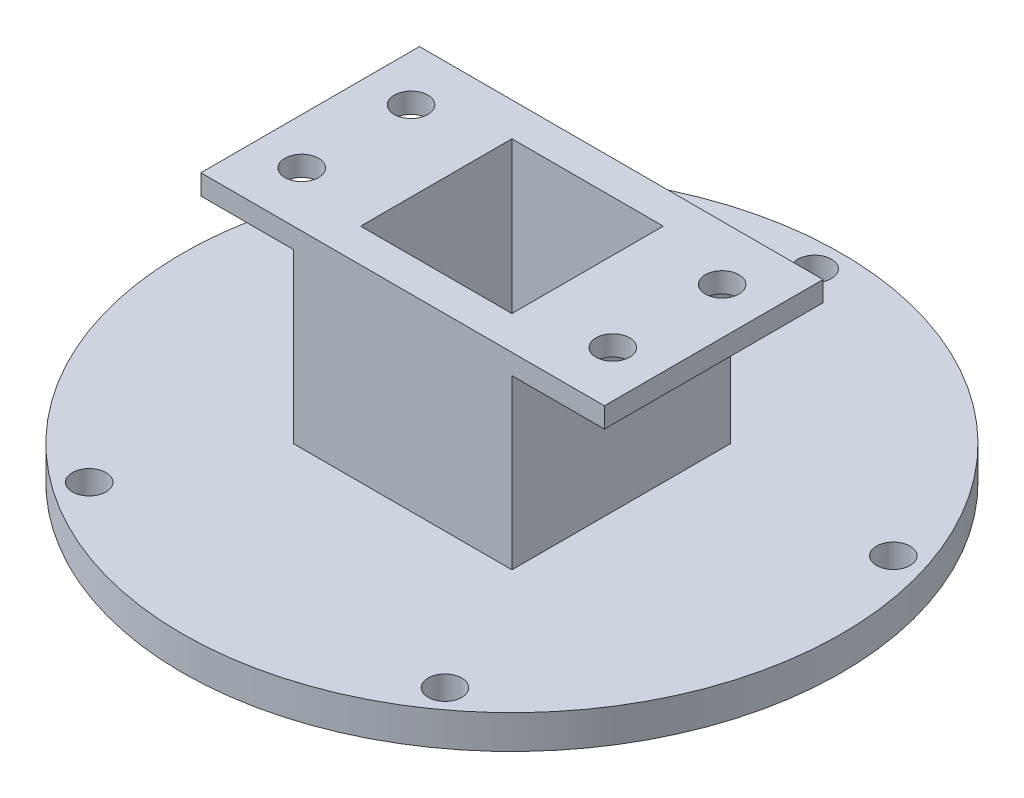
SolidWorks part; units mm, degrees
ref_plane "Front Plane" through (0, 0, 0) normal (0, 0, 1) x (1, 0, 0)
ref_plane "Top Plane" through (0, 0, 0) normal (0, 1, 0) x (1, 0, 0)
ref_plane "Right Plane" through (0, 0, 0) normal (1, 0, 0) x (0, 0, -1)
sketch "Sketch1" plane through (0, 0, 0) normal (0, 1, 0) x (1, 0, 0)
  line L0 (0, 0) -> (0, 90) construction
  circle A0 centre (0, 0) radius 98
  circle A1 centre (0, 90) radius 5
  circle A2 centre (85.5951, 27.8115) radius 5
  circle A3 centre (52.9007, -72.8115) radius 5
  circle A4 centre (-52.9007, -72.8115) radius 5
  circle A5 centre (-85.5951, 27.8115) radius 5
  point P15 (0, 0)
extrude "Boss-Extrude1" add sketch "Sketch1" along normal blind 10
sketch "Sketch2" plane through (0, 10, 0) normal (0, 1, 0) x (1, 0, 0)
  line L1 (-32.5, 32.5) -> (32.5, 32.5)
  line L2 (-32.5, 32.5) -> (-32.5, -32.5)
  line L3 (-32.5, -32.5) -> (32.5, -32.5)
  line L4 (32.5, 32.5) -> (32.5, -32.5)
  line L5 (-32.5, 32.5) -> (32.5, -32.5) construction
  line L6 (-32.5, -32.5) -> (32.5, 32.5) construction
  point P0 (0, 0)
  dimension "D1" = 65
  dimension "D2" = 65
extrude "Boss-Extrude2" add sketch "Sketch2" along normal blind 50
sketch "Sketch3" plane through (0, 60, 0) normal (0, 1, 0) x (1, 0, 0)
  line L0 (0, 0) -> (-60, 0) construction
  line L1 (-60, 32.5) -> (60, 32.5)
  line L2 (-60, 32.5) -> (-60, -32.5)
  line L3 (-60, -32.5) -> (60, -32.5)
  line L4 (60, 32.5) -> (60, -32.5)
  line L5 (-60, 32.5) -> (60, -32.5) construction
  line L6 (-60, -32.5) -> (60, 32.5) construction
  line L7 (-32.5, 32.5) -> (-32.5, 0) construction
  line L8 (-32.5, 32.5) -> (-32.5, -32.5) construction
  line L9 (-32.5, 16.25) -> (-60, 16.25) construction
  line L10 (0, 0) -> (0, 32.5) construction
  circle A0 centre (-46.25, 16.25) radius 5
  circle A1 centre (46.25, 16.25) radius 5
  circle A2 centre (46.25, -16.25) radius 5
  circle A3 centre (-46.25, -16.25) radius 5
  point P0 (0, 0)
  dimension "D3" = 27.5
  dimension "D1" = 120
  dimension "D2" = 65
extrude "Boss-Extrude3" add sketch "Sketch3" along normal blind 6
sketch "Sketch4" plane through (0, 66, 0) normal (0, 1, 0) x (1, 0, 0)
  line L1 (-22.5, 22.5) -> (22.5, 22.5)
  line L2 (-22.5, 22.5) -> (-22.5, -22.5)
  line L3 (-22.5, -22.5) -> (22.5, -22.5)
  line L4 (22.5, 22.5) -> (22.5, -22.5)
  line L5 (-22.5, 22.5) -> (22.5, -22.5) construction
  line L6 (-22.5, -22.5) -> (22.5, 22.5) construction
  point P0 (0, 0)
  dimension "D1" = 45
  dimension "D2" = 45
extrude "Cut-Extrude1" cut sketch "Sketch4" against normal through all
